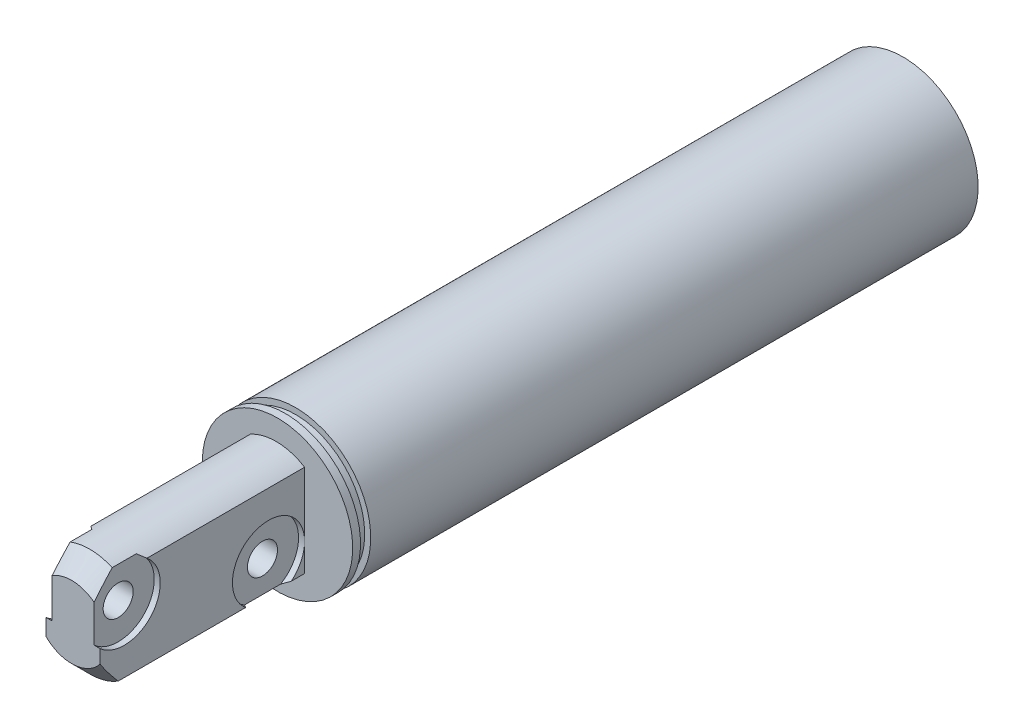
SolidWorks part; units mm, degrees
material "1060 合金"
ref_plane "前视基准面" through (0, 0, 0) normal (0, 0, 1) x (1, 0, 0)
ref_plane "上视基准面" through (0, 0, 0) normal (0, 1, 0) x (1, 0, 0)
ref_plane "右视基准面" through (0, 0, 0) normal (1, 0, 0) x (0, 0, -1)
sketch "草图1" plane through (0, 0, 0) normal (0, 0, 1) x (1, 0, 0)
  circle A0 centre (0, 0) radius 12.5
  dimension "D1" = 25
extrude "凸台-拉伸1" add sketch "草图1" along normal blind 104
sketch "草图6" plane through (0, 0, 0) normal (0, 1, 0) x (1, 0, 0)
  line L0 (0, 0) -> (0, -36.1312) construction
  line L1 (-12.5, 0) -> (-12.5, -104) construction
  line L2 (-12.5, -102.7) -> (-11.5, -102.7)
  line L3 (-12.5, -102.7) -> (-12.5, -101)
  line L4 (-12.5, -101) -> (-11.5, -101)
  line L5 (-11.5, -102.7) -> (-11.5, -101)
  line L6 (12.5, 0) -> (-12.5, 0) construction
  dimension "D1" = 1.7
  dimension "D2" = 101
  dimension "D3" = 1
revolve "切除-旋转1" cut sketch "草图6" angle 360 about L0
sketch "草图7" plane through (0, 0, 0) normal (0, 0, -1) x (-1, 0, 0)
  circle A0 centre (0, 0) radius 8
  circle A1 centre (0, 0) radius 12.5 construction
  dimension "D1" = 16
extrude "凸台-拉伸2" add sketch "草图7" along normal blind 2
hole_wizard "M8 螺纹孔1" positions "草图4" profile "草图5" tap size "M8" standard "GB"
sketch "草图4" plane through (0, 0, -2) normal (0, 0, -1) x (-1, 0, 0)
  point P0 (0, 0)
sketch "草图5" plane through (0, 0, -2) normal (1, 0, 0) x (0, 1, 0)
  line L0 (0, 0) -> (0, 84.2929)
  line L1 (0, 84.2929) -> (3.4, 82.25)
  line L2 (3.4, 82.25) -> (3.4, 0)
  line L5 (3.4, 0) -> (0, 0)
  line L10 (0, 84.2929) -> (-3.4, 82.25) construction
  line L11 (0, -6.35) -> (0, 107.95) construction
  dimension "螺纹孔钻头直径" = 6.8
  dimension "螺纹孔钻头深度" = 82.25
  dimension "导头角度" = 118
cosmetic thread "孔螺蚊线1" parameters "D1"=26, "D2"=8
sketch "草图9" plane through (0, 0, 104) normal (0, 0, 1) x (1, 0, 0)
  circle A0 centre (-0.2311, 0) radius 9
  dimension "D1" = 18
extrude "凸台-拉伸3" add sketch "草图9" along normal blind 34
sketch "草图8" plane through (0, 0, 0) normal (0, 1, 0) x (0, 0, -1)
  line L0 (0, 0) -> (-145.8395, 0) construction
  line L3 (-104, -14.9439) -> (-138, -4.5) construction
  line L4 (-104, 4.5) -> (-138, 4.5)
  line L5 (-104, 4.5) -> (-104, 14.9439)
  line L6 (-104, 14.9439) -> (-138, 14.9439)
  line L7 (-138, 4.5) -> (-138, 14.9439)
  line L8 (-104, 4.5) -> (-138, 14.9439) construction
  line L9 (-104, 14.9439) -> (-138, 4.5) construction
  line L11 (-104, -4.5) -> (-138, -14.9439) construction
  line L12 (-138, -4.5) -> (-138, -14.9439)
  line L13 (-104, -14.9439) -> (-138, -14.9439)
  line L14 (-104, -4.5) -> (-104, -14.9439)
  line L15 (-104, -4.5) -> (-138, -4.5)
  line L16 (-138, 9.2311) -> (-138, -8.7689) construction
  line L17 (-104, 12.5) -> (-104, -12.5) construction
  point P3 (-121, 9.722)
  point P18 (-121, -9.722)
  dimension "D1" = 9
extrude "切除-拉伸1" cut sketch "草图8" against normal through all both and the other way through all
sketch "草图10" plane through (4.5, 0, 0) normal (1, 0, 0) x (0, 0, -1)
  line L0 (-138, 7.6562) -> (-138, -7.6562) construction
  circle A0 centre (-134, 0) radius 2.5
  circle A1 centre (-110, 0) radius 2.5
  dimension "D2" = 5
  dimension "D3" = 19
  dimension "D1" = 4
extrude "切除-拉伸2" [suppressed] cut sketch "草图10" against normal through all
chamfer "倒角1" distance 3 angle 45 2 edges at (0.0358, 8.996, 138) (0.0358, -8.996, 138)
hole_wizard "Ø5.0 (5) 直径孔1" positions "草图12" profile "草图11" hole size "Ø5.0" standard "GB" end condition up to next
sketch "草图12" plane through (4.5, 0, 0) normal (1, 0, 0) x (0, 0, -1)
  line L0 (-138, 0) -> (-106.462, 0) construction
  line L1 (-138, 3.6901) -> (-138, -3.6901) construction
  point P0 (-110, -3)
  point P2 (-134, 3)
  dimension "D1" = 3
  dimension "D2" = 3
  dimension "D3" = 24
  dimension "D4" = 4
sketch "草图11" plane through (4.5, -3, 110) normal (0, 1, 0) x (0, 0, -1)
  line L0 (0, 0) -> (0, 9)
  line L1 (0, 9) -> (2.5, 9)
  line L2 (2.5, 9) -> (2.5, 0)
  line L5 (2.5, 0) -> (0, 0)
  line L11 (0, -6.35) -> (0, 107.95) construction
  dimension "通孔孔直径" = 5
  dimension "通孔孔深度" = 9
sketch "草图13" plane through (4.5, 0, 0) normal (1, 0, 0) x (0, 0, -1)
  circle A0 centre (-134, 3) radius 6
  circle A1 centre (-110, -3) radius 6
  dimension "D1" = 12
extrude "切除-拉伸3" cut sketch "草图13" against normal blind 1
mirror "镜向1" about plane through (0, 0, 0) normal (1, 0, 0) of "切除-拉伸3"
